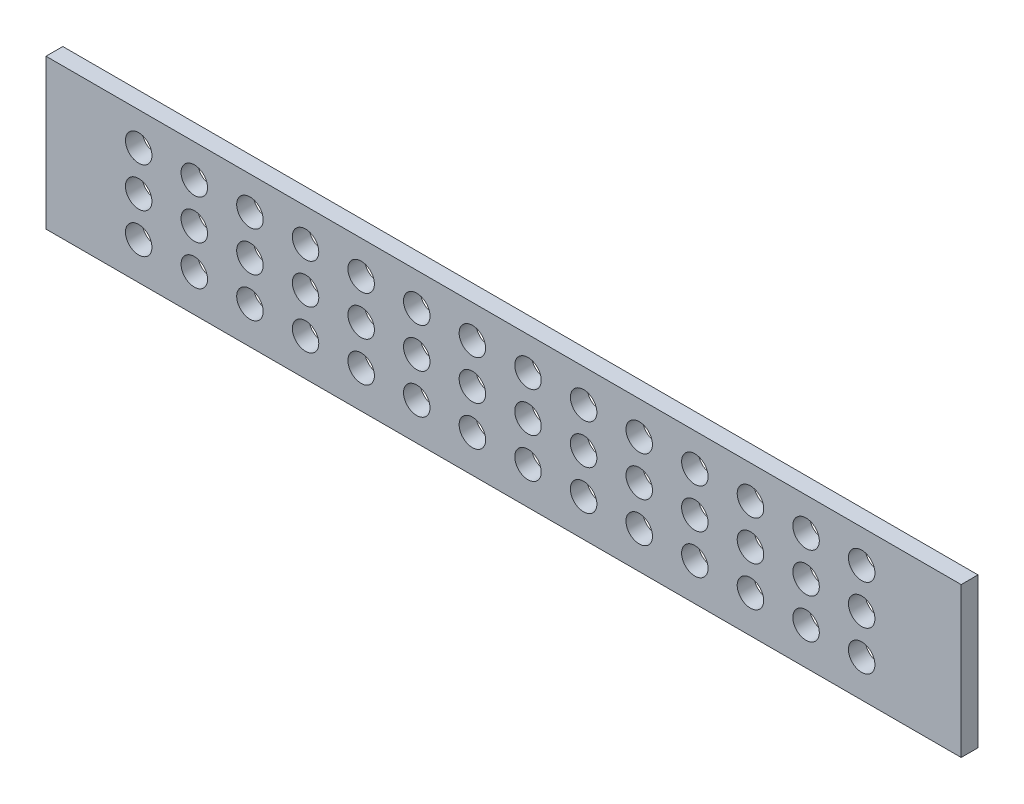
SolidWorks part; units mm, degrees
material "Custom Plastic"
ref_plane "X-Y Datum" through (0, 0, 0) normal (0, 0, 1) x (1, 0, 0)
ref_plane "X-Z Datum" through (0, 0, 0) normal (0, 1, 0) x (1, 0, 0)
ref_plane "Y-Z Datum" through (0, 0, 0) normal (1, 0, 0) x (0, 0, -1)
sketch "Sketch1" plane through (0, 0, 0) normal (0, 0, 1) x (1, 0, 0)
  line L1 (-172.785, -28.275) -> (172.785, -28.275)
  line L2 (-172.785, -28.275) -> (-172.785, 28.275)
  line L3 (-172.785, 28.275) -> (172.785, 28.275)
  line L4 (172.785, -28.275) -> (172.785, 28.275)
  line L5 (-172.785, -28.275) -> (172.785, 28.275) construction
  line L6 (-172.785, 28.275) -> (172.785, -28.275) construction
  point P0 (0, 0)
  dimension "D1" = 345.57
  dimension "D2" = 56.55
extrude "Boss-Extrude1" add sketch "Sketch1" along normal blind 6.35
sketch "Sketch2" plane through (0, 0, 6.35) normal (0, 0, 1) x (1, 0, 0)
  line L0 (172.785, -28.275) -> (172.785, 28.275) construction
  line L1 (-172.785, 28.275) -> (-172.785, -28.275) construction
  line L2 (-172.785, -28.275) -> (172.785, -28.275) construction
  line L3 (172.785, 28.275) -> (-172.785, 28.275) construction
  line L9 (-142.785, 20.775) -> (142.785, 20.775)
  line L10 (-142.785, 20.775) -> (-142.785, -20.775)
  line L11 (-142.785, -20.775) -> (142.785, -20.775)
  line L12 (142.785, 20.775) -> (142.785, -20.775)
  circle A0 centre (-137.785, 15.775) radius 5
  dimension "D3" = 10
  dimension "D1" = 30
  dimension "D2" = 7.5
  dimension "D4" = 30
  dimension "D5" = 7.5
extrude "Cut-Extrude1" cut sketch "Sketch2" against normal blind 10 contours A0
pattern_linear "LPattern1" count 14 spacing 21 along (1, 0, 0) count 3 spacing 15 along (0, -1, 0) of "Cut-Extrude1"
